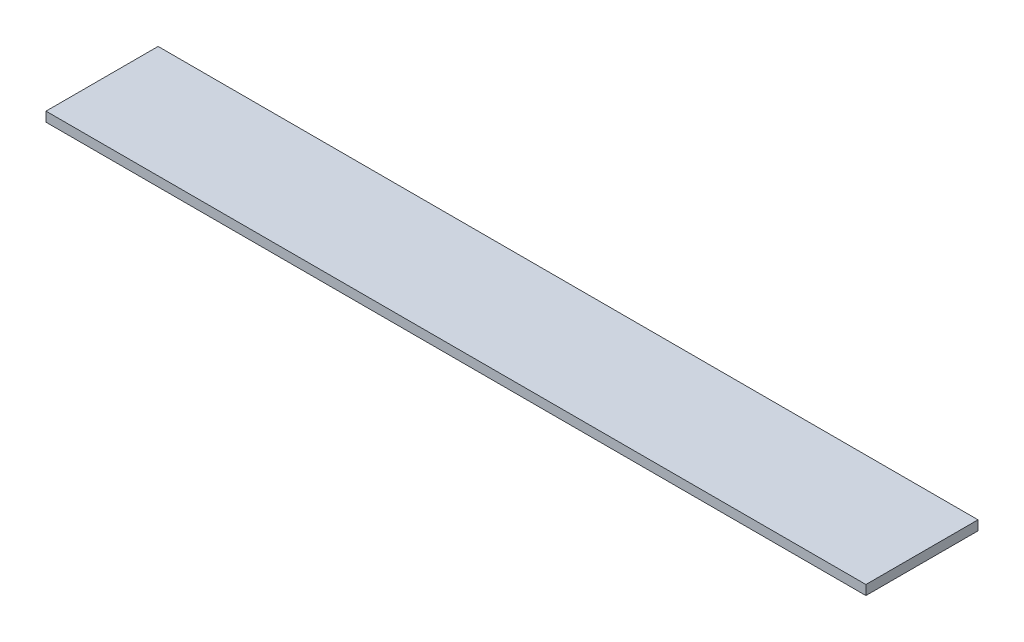
SolidWorks part; units mm, degrees
ref_plane "Front Plane" through (0, 0, 0) normal (0, 0, 1) x (1, 0, 0)
ref_plane "Top Plane" through (0, 0, 0) normal (0, 1, 0) x (1, 0, 0)
ref_plane "Right Plane" through (0, 0, 0) normal (1, 0, 0) x (0, 0, -1)
sketch "Sketch1" plane through (0, 0, 0) normal (0, 1, 0) x (1, 0, 0)
  line L1 (64, -8.75) -> (-64, -8.75)
  line L2 (64, -8.75) -> (64, 8.75)
  line L3 (64, 8.75) -> (-64, 8.75)
  line L4 (-64, -8.75) -> (-64, 8.75)
  line L5 (64, -8.75) -> (-64, 8.75) construction
  line L6 (64, 8.75) -> (-64, -8.75) construction
  point P0 (0, 0)
  dimension "D1" = 128
  dimension "D2" = 17.5
extrude "Boss-Extrude1" add sketch "Sketch1" along normal blind 1.5
